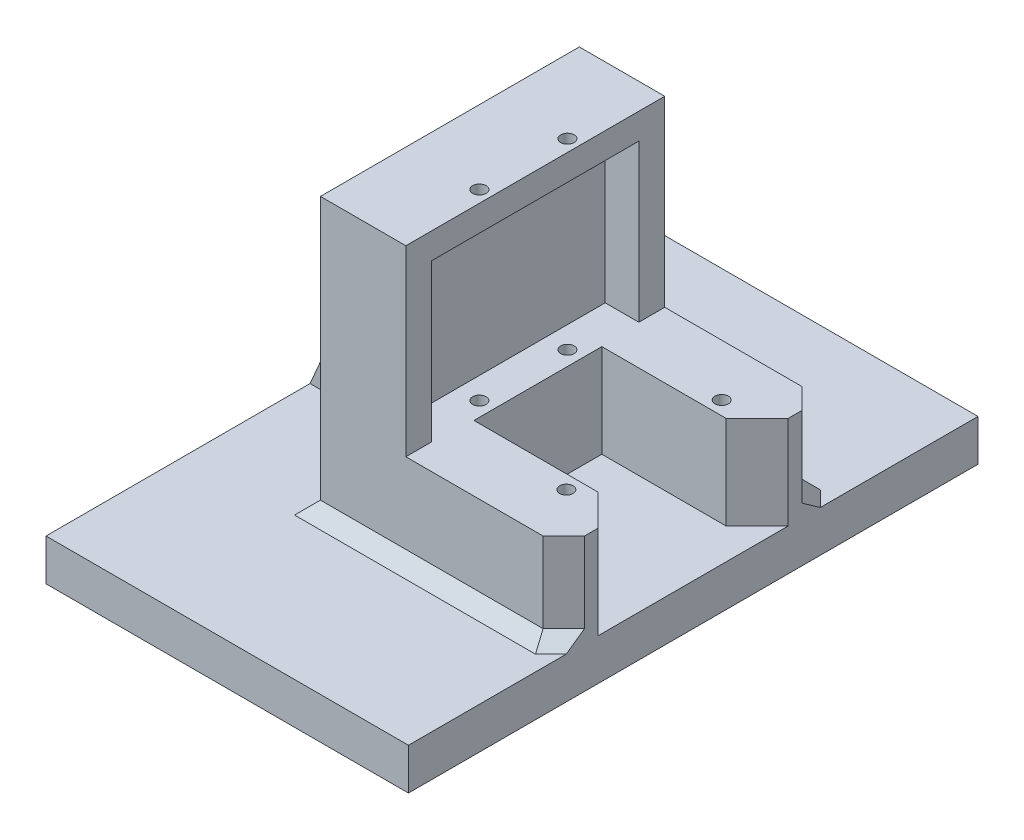
SolidWorks part; units mm, degrees
ref_plane "Front Plane" through (0, 0, 0) normal (0, 0, 1) x (1, 0, 0)
ref_plane "Top Plane" through (0, 0, 0) normal (0, 1, 0) x (1, 0, 0)
ref_plane "Right Plane" through (0, 0, 0) normal (1, 0, 0) x (0, 0, -1)
sketch "Sketch1" plane through (0, 0, 0) normal (0, 1, 0) x (1, 0, 0)
  line L1 (0, 0) -> (70, 0)
  line L2 (0, 0) -> (0, 110)
  line L3 (0, 110) -> (70, 110)
  line L4 (70, 0) -> (70, 110)
  dimension "D1" = 110
  dimension "D2" = 70
extrude "Boss-Extrude1" add sketch "Sketch1" along normal blind 8
sketch "Sketch2" plane through (0, 8, 0) normal (0, 1, 0) x (1, 0, 0)
  line L0 (70, 0) -> (70, 110) construction
  line L1 (70, 67.35) -> (40, 67.35)
  line L2 (70, 67.35) -> (70, 80)
  line L3 (70, 80) -> (23, 80)
  line L7 (70, 42.65) -> (40, 42.65)
  line L8 (70, 42.65) -> (70, 30)
  line L9 (70, 30) -> (23, 30)
  line L10 (23, 80) -> (23, 30)
  line L12 (40, 67.35) -> (40, 42.65)
  point P3 (0, 49.233)
  point P6 (70, 55)
  point P7 (23, 55)
  point P11 (0, 0)
  point P12 (0, 0)
  dimension "D1" = 24.7
  dimension "D2" = 30
  dimension "D3" = 17
  dimension "D4" = 12.65
extrude "Boss-Extrude2" add sketch "Sketch2" along normal blind 18
sketch "Sketch3" plane through (0, 26, 0) normal (0, 1, 0) x (1, 0, 0)
  line L0 (60.5, 70) -> (60.5, 55) construction
  line L1 (70, 42.65) -> (70, 67.35) construction
  line L2 (70, 67.35) -> (70, 80) construction
  line L3 (37.2, 63.5) -> (37.2, 55) construction
  circle A0 centre (60.5, 70) radius 1.3
  circle A1 centre (37.2, 63.5) radius 1.3
  point P8 (70, 55)
  dimension "D1" = 15
  dimension "D2" = 9.5
  dimension "D3" = 2.6
  dimension "D4" = 8.5
  dimension "D5" = 23.3
extrude "Cut-Extrude1" cut sketch "Sketch3" against normal through all
ref_plane "Plane1" through (0, 0, -55) normal (0, 0, 1) x (1, 0, 0)
sketch "Sketch4" plane through (0, 26, 0) normal (0, 1, 0) x (1, 0, 0)
  circle A0 centre (37.2, 63.5) radius 2.45
  circle A1 centre (60.5, 70) radius 2.45
  dimension "D1" = 4.9
extrude "Cut-Extrude3" cut sketch "Sketch4" against normal through all from offset 6 offset against normal yes
mirror "Mirror3" about plane through (0, 0, -55) normal (0, 0, 1) of "Cut-Extrude3", "Cut-Extrude1"
chamfer "Chamfer2" distance 6 angle 45 2 edges at (70, 17, -42.65) (70, 17, -67.35)
chamfer "Chamfer7" distance 4 angle 45 2 edges at (70, 17, -80) (70, 17, -30)
chamfer "Chamfer6" distance 2.5 angle 45 5 edges at (44.5, 8, -80) (23, 8, -55) (44.5, 8, -30) (68, 8, -78) (68, 8, -32)
sketch "Sketch6" plane through (0, 26, 0) normal (0, 1, 0) x (1, 0, 0)
  line L0 (23, 30) -> (66, 30) construction
  line L1 (23, 80) -> (33, 80)
  line L2 (23, 80) -> (23, 30)
  line L3 (23, 30) -> (33, 30)
  line L4 (33, 80) -> (33, 30)
  line L5 (40, 42.65) -> (40, 67.35) construction
  dimension "D1" = 7
extrude "Boss-Extrude4" add sketch "Sketch6" along normal blind 30.3
sketch "Sketch7" plane through (0, 56.3, 0) normal (0, 1, 0) x (1, 0, 0)
  line L0 (66, 80) -> (23, 80) construction
  line L1 (23, 30) -> (39.5, 30)
  line L2 (23, 30) -> (23, 80)
  line L3 (23, 80) -> (39.5, 80)
  line L4 (39.5, 30) -> (39.5, 80)
  circle A0 centre (37.2, 63.5) radius 1.3
  circle A1 centre (37.2, 46.5) radius 1.3
  circle A2 centre (37.2, 46.5) radius 1.3 construction
  dimension "D1" = 16.5
extrude "Boss-Extrude5" add sketch "Sketch7" along normal blind 5
sketch "Sketch8" plane through (0, 0, -30) normal (0, 0, 1) x (1, 0, 0)
  line L0 (33, 56.3) -> (33, 26)
  line L1 (33, 26) -> (39.5, 26)
  line L2 (33, 26) -> (66, 26) construction
  line L3 (39.5, 26) -> (39.5, 56.3)
  line L4 (39.5, 56.3) -> (33, 56.3)
extrude "Boss-Extrude6" add sketch "Sketch8" against normal blind 5
mirror "Mirror4" about plane through (0, 0, -55) normal (0, 0, 1) of "Boss-Extrude6"
sketch "Sketch9" plane through (0, 0, -55) normal (0, 0, 1) x (1, 0, 0)
  line L0 (0, 8) -> (23, 8)
  line L1 (67.0355, 8) -> (20.5, 8) construction
  line L2 (23, 8) -> (23, 61.3)
  line L3 (23, 61.3) -> (0, 8)
  line L4 (23, 61.3) -> (23, 10.5) construction
extrude "Boss-Extrude7" add sketch "Sketch9" along normal blind 4 and the other way blind 4
